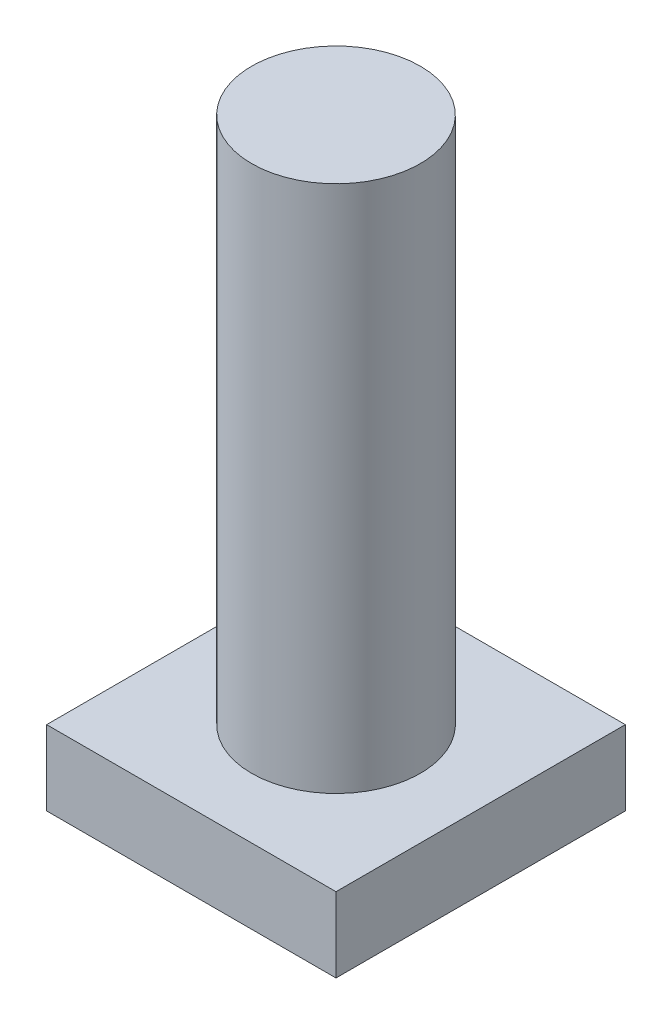
SolidWorks part; units mm, degrees
ref_plane "前视" through (0, 0, 0) normal (0, 0, 1) x (1, 0, 0)
ref_plane "上视" through (0, 0, 0) normal (0, 1, 0) x (1, 0, 0)
ref_plane "右视" through (0, 0, 0) normal (1, 0, 0) x (0, 0, -1)
sketch "草图1" plane through (0, 0, 0) normal (0, 1, 0) x (1, 0, 0)
  line L0 (0, 96.9306) -> (0, -101.3275) construction
  line L1 (-119.7143, 0) -> (134.9034, 0) construction
  line L3 (-6, 6) -> (6, 6)
  line L4 (-6, 6) -> (-6, -6)
  line L5 (-6, -6) -> (6, -6)
  line L6 (6, 6) -> (6, -6)
  dimension "D1" = 12
  dimension "D2" = 12
extrude "拉伸1" add sketch "草图1" along normal blind 3.1
sketch "草图2" plane through (0, 3.1, 0) normal (0, 1, 0) x (-1, 0, 0)
  line L0 (-6, 0) -> (8.7109, 0) construction
  line L1 (-6, 6) -> (-6, -6) construction
  line L2 (0, -7.8518) -> (0, 10.0992) construction
  circle A0 centre (0, 0) radius 3.5
  dimension "D1" = 7
extrude "拉伸2" add sketch "草图2" along normal offset from surface (21.9 mm away) 25 up to face at (0, 0, 0)
sketch "草图3" plane through (-6, 0, 0) normal (-1, 0, 0) x (0, 0, 1)
  line L0 (0, -6.9925) -> (0, 14.8526) construction
sketch "草图4" plane through (0, 25, 0) normal (0, 1, 0) x (-1, 0, 0)
  line L0 (0, -4.1469) -> (0, 4.9476) construction
  line L1 (-3.9082, 0) -> (5.1305, 0) construction
sketch "草图5" plane through (0, 0, 0) normal (0, -1, 0) x (1, 0, 0)
  line L0 (10.1949, 0) -> (-13.2034, 0) construction
  line L1 (0, 8.665) -> (0, -9.2576) construction
